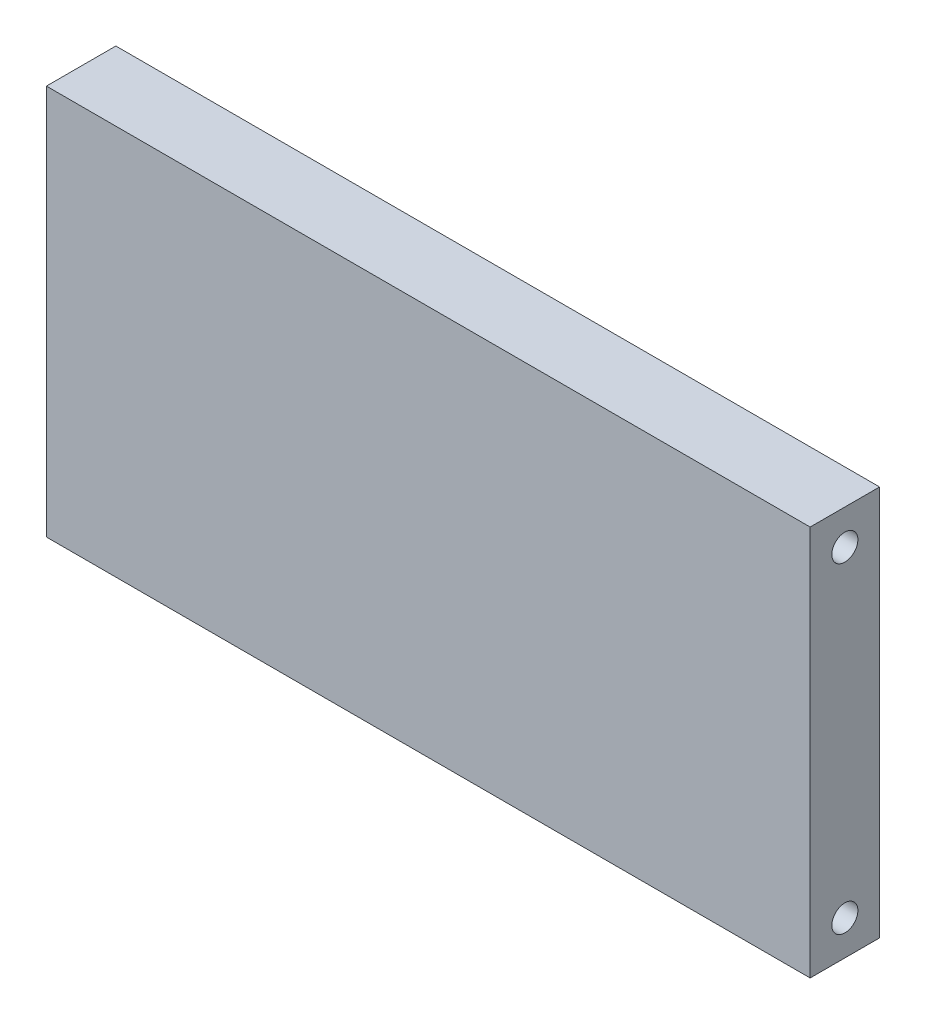
SolidWorks part; units mm, degrees
ref_plane "Front Plane" through (0, 0, 0) normal (0, 0, 1) x (1, 0, 0)
ref_plane "Top Plane" through (0, 0, 0) normal (0, 1, 0) x (1, 0, 0)
ref_plane "Right Plane" through (0, 0, 0) normal (1, 0, 0) x (0, 0, -1)
sketch "Sketch1" plane through (0, 0, 0) normal (0, 0, 1) x (1, 0, 0)
  line L1 (0, 0) -> (88, 0)
  line L2 (0, 0) -> (0, 45)
  line L3 (0, 45) -> (88, 45)
  line L4 (88, 0) -> (88, 45)
  dimension "D1" = 88
  dimension "D2" = 45
extrude "Boss-Extrude1" add sketch "Sketch1" along normal blind 8
sketch "Sketch2" plane through (0, 0, 0) normal (-1, 0, 0) x (0, 0, 1)
  line L0 (0, 22.5) -> (8, 22.5) construction
  line L1 (0, 45) -> (0, 0) construction
  line L2 (8, 45) -> (8, 0) construction
  line L5 (4, 45) -> (4, 0) construction
  line L6 (8, 45) -> (0, 45) construction
  line L7 (8, 0) -> (0, 0) construction
  circle A0 centre (4, 41) radius 1.5
  circle A1 centre (4, 4) radius 1.5
  dimension "D1" = 4
  dimension "D2" = 3
extrude "Cut-Extrude1" cut sketch "Sketch2" against normal blind 144
